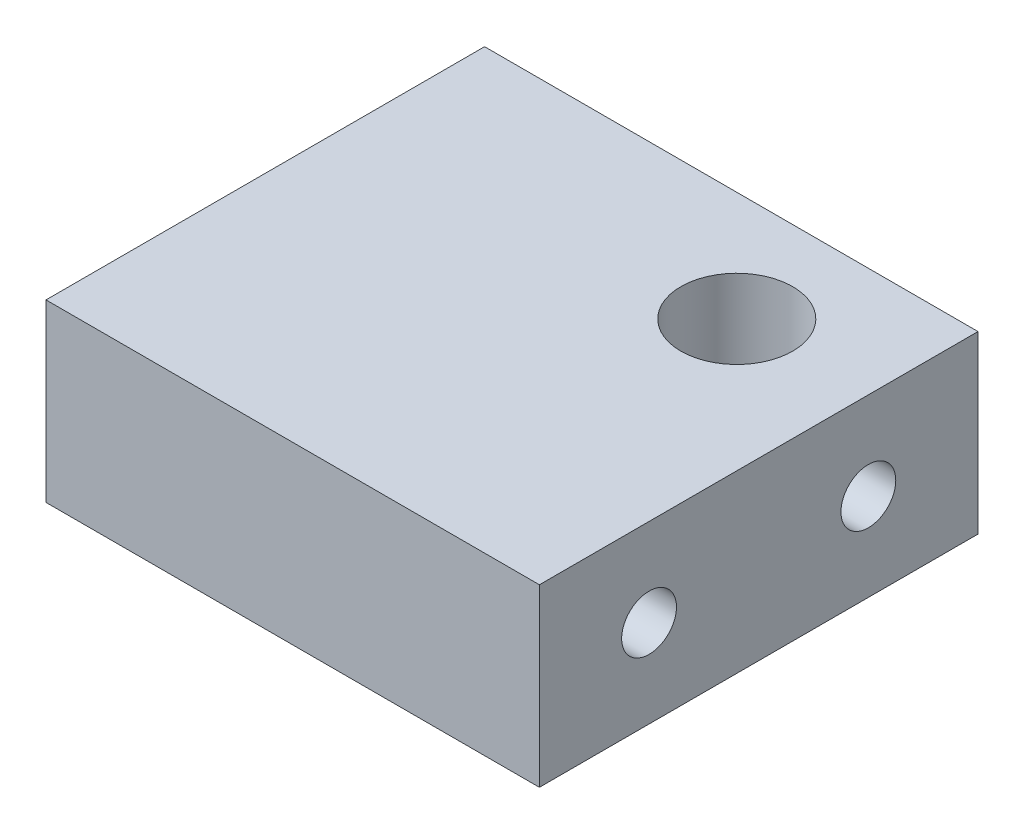
SolidWorks part; units mm, degrees
ref_plane "前视基准面" through (0, 0, 0) normal (0, 0, 1) x (1, 0, 0)
ref_plane "上视基准面" through (0, 0, 0) normal (0, 1, 0) x (1, 0, 0)
ref_plane "右视基准面" through (0, 0, 0) normal (1, 0, 0) x (0, 0, -1)
sketch "草图1" plane through (0, 0, 0) normal (0, 1, 0) x (1, 0, 0)
  line L1 (-22.5, 20) -> (22.5, 20)
  line L2 (-22.5, 20) -> (-22.5, -20)
  line L3 (-22.5, -20) -> (22.5, -20)
  line L4 (22.5, 20) -> (22.5, -20)
  line L5 (-22.5, 20) -> (22.5, -20) construction
  line L6 (-22.5, -20) -> (22.5, 20) construction
  point P0 (0, 0)
  dimension "D1" = 45
  dimension "D2" = 40
extrude "凸台-拉伸1" add sketch "草图1" along normal blind 16
sketch "草图2" plane through (22.5, 0, 0) normal (1, 0, 0) x (0, 0, -1)
  line L0 (-20, 8) -> (-18.8353, 8)
  line L1 (-20, 16) -> (-20, 0) construction
  line L2 (-10, 8) -> (10, 8)
  point P8 (0, 8)
  dimension "D1" = 20
  dimension "D2" = 0
hole_wizard "M6 螺纹孔1" positions "3D草图1" profile "草图3" tap size "M6" standard "GB" end condition up to next
sketch3d "3D草图1"
  point P0 (22.5, 8, 10)
sketch "草图3" plane through (22.5, 8, 10) normal (0, 1, 0) x (0, 0, -1)
  line L0 (0, 0) -> (0, 45)
  line L1 (0, 45) -> (2.5, 45)
  line L2 (2.5, 45) -> (2.5, 0)
  line L5 (2.5, 0) -> (0, 0)
  line L11 (0, -6.35) -> (0, 107.95) construction
  dimension "通孔螺纹孔钻头直径" = 5
  dimension "通孔螺纹孔钻头深度" = 45
cosmetic thread "孔螺蚊线1"
sketch "草图5" plane through (0, 16, 0) normal (0, 1, 0) x (1, 0, 0)
  line L0 (22.5, -20) -> (22.5, 20) construction
  circle A0 centre (10.5, 10) radius 5.1
  dimension "D3" = 10.2
  dimension "D1" = 12
  dimension "D2" = 0
extrude "切除-拉伸1" cut sketch "草图5" against normal blind 50
hole_wizard "M6 螺纹孔2" positions "3D草图2" profile "草图4" tap size "M6" standard "GB"
sketch3d "3D草图2"
  point P0 (22.5, 8, -10)
sketch "草图4" plane through (22.5, 8, -10) normal (0, 1, 0) x (0, 0, -1)
  line L0 (0, 0) -> (0, 11.5022)
  line L1 (0, 11.5022) -> (2.5, 10)
  line L2 (2.5, 10) -> (2.5, 0)
  line L5 (2.5, 0) -> (0, 0)
  line L10 (0, 11.5022) -> (-2.5, 10) construction
  line L11 (0, -6.35) -> (0, 107.95) construction
  dimension "螺纹孔钻头直径" = 5
  dimension "螺纹孔钻头深度" = 10
  dimension "导头角度" = 118
cosmetic thread "孔螺蚊线2"
